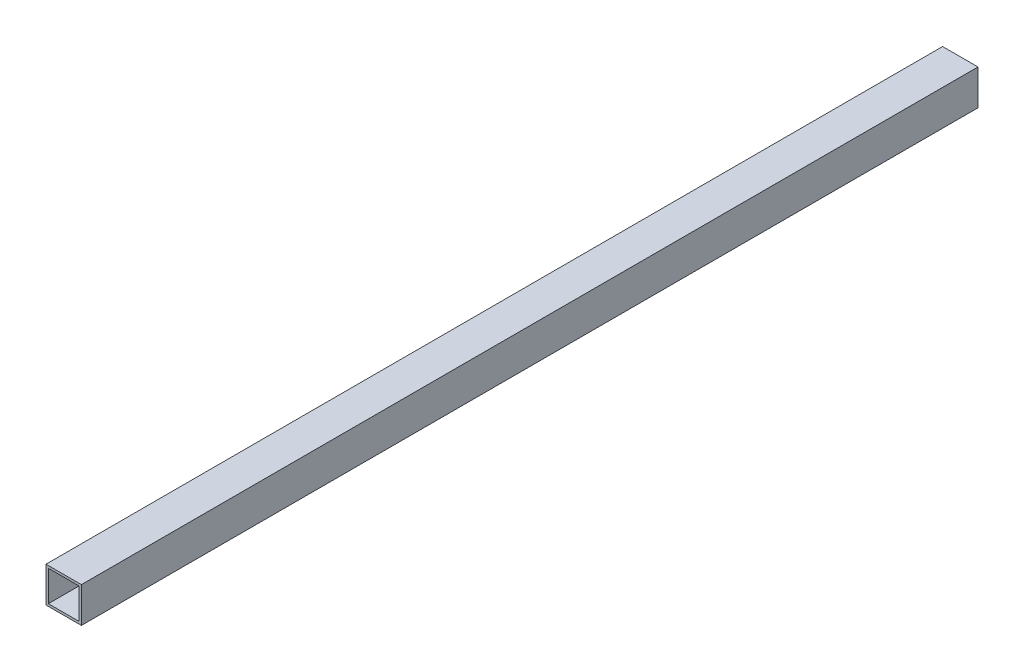
SolidWorks part; units mm, degrees
ref_plane "Front Plane" through (0, 0, 0) normal (0, 0, 1) x (1, 0, 0)
ref_plane "Top Plane" through (0, 0, 0) normal (0, 1, 0) x (1, 0, 0)
ref_plane "Right Plane" through (0, 0, 0) normal (1, 0, 0) x (0, 0, -1)
sketch "Sketch1" plane through (0, 0, 0) normal (0, 0, 1) x (1, 0, 0)
  line L0 (-16.51, 16.51) -> (16.51, 16.51)
  line L1 (-19.05, -19.05) -> (19.05, -19.05)
  line L2 (-19.05, -19.05) -> (-19.05, 19.05)
  line L3 (-19.05, 19.05) -> (19.05, 19.05)
  line L4 (19.05, -19.05) -> (19.05, 19.05)
  line L5 (-19.05, -19.05) -> (19.05, 19.05) construction
  line L6 (-19.05, 19.05) -> (19.05, -19.05) construction
  line L7 (16.51, -16.51) -> (16.51, 16.51)
  line L8 (-16.51, -16.51) -> (16.51, -16.51)
  line L9 (-16.51, -16.51) -> (-16.51, 16.51)
  point P0 (0, 0)
  dimension "D1" = 38.1
  dimension "D2" = 2.54
extrude "Boss-Extrude1" add sketch "Sketch1" along normal mid plane 965.2
